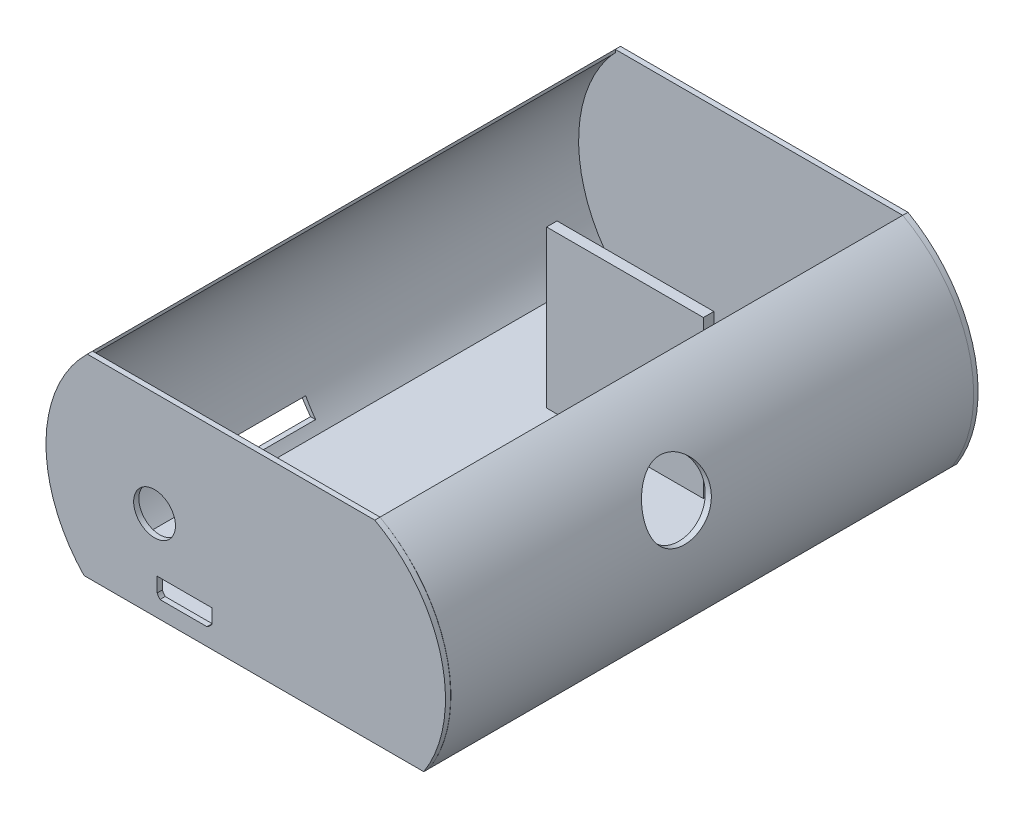
SolidWorks part; units mm, degrees
ref_plane "Front Plane" through (0, 0, 0) normal (0, 0, 1) x (1, 0, 0)
ref_plane "Top Plane" through (0, 0, 0) normal (0, 1, 0) x (1, 0, 0)
ref_plane "Right Plane" through (0, 0, 0) normal (1, 0, 0) x (0, 0, -1)
sketch "Sketch11" plane through (0, 0, 0) normal (0, 0, 1) x (1, 0, 0)
  line L0 (-50.9258, 31.4368) -> (4.0742, 31.4368)
  line L3 (13.439, -5.5632) -> (-51.561, -5.5632)
  line L4 (-51.013, 30.8355) -> (3.987, 30.8355)
  line L9 (3.987, 30.8355) -> (-51.013, 30.8355)
  line L11 (-51.561, -4.5645) -> (13.439, -4.5645)
  arc A0 (-50.9258, 31.4368) -> (-51.561, -5.5632) centre (-32.98, 12.6232) ccw
  arc A1 (4.0742, 31.4368) -> (13.439, -5.5632) centre (-8.3621, 8.604) cw
  arc A3 (-51.013, 30.8355) -> (-51.561, -4.5645) centre (-31.0337, 12.822) ccw
  arc A4 (3.987, 30.8355) -> (13.439, -4.5645) centre (-10.2712, 8.0666) cw
  point P6 (-46.0039, -5.5632)
  point P8 (4.0848, 31.4053)
  dimension "D3" = 26
  dimension "D4" = 65
  dimension "D5" = 55
  dimension "D6" = 37
  dimension "D7" = 65
  dimension "D9" = 0.9987
  dimension "D18" = 55
  dimension "D23" = 35.4
extrude "Boss-Extrude6" add sketch "Sketch11" along normal blind 100 and the other way blind 0.001
ref_plane "front" through (0, 0, 100) normal (0, 0, 1) x (1, 0, 0)
ref_plane "Plane9" through (0, 31.4368, 0) normal (0, -1, 0) x (-1, 0, 0)
sketch "Buttons" plane through (0, 31.4368, 0) normal (0, -1, 0) x (-1, 0, 0)
  line L5 (50.7065, 0.001) -> (-4.2935, 0.001)
  line L6 (50.7065, 0.001) -> (50.7065, -99.999)
  line L7 (50.7065, -99.999) -> (-4.2935, -99.999)
  line L8 (-4.2935, 0.001) -> (-4.2935, -99.999)
  line L10 (-13.439, 0.001) -> (51.561, 0.001) construction
  dimension "D3" = 0
  dimension "D11" = 55
  dimension "D12" = 100
ref_plane "Plane5" through (17.6379, 0, 0) normal (1, 0, 0) x (0, 0, -1)
sketch "Sketch19" plane through (17.6379, 0, 0) normal (1, 0, 0) x (0, 0, -1)
  line L2 (-100, 31.4368) -> (-100, -5.5632) construction
  line L3 (0.001, -5.5632) -> (-100, -5.5632) construction
  circle A0 centre (-55.2, 17.4368) radius 6.25
  dimension "D1" = 23
  dimension "D3" = 12.5
  dimension "D2" = 44.8
extrude "side button" cut sketch "Sketch19" against normal blind 10
ref_plane "sd card" through (-58.98, 0, 0) normal (-1, 0, 0) x (0, 0, 1)
sketch "Sketch21" plane through (-58.98, 0, 0) normal (-1, 0, 0) x (0, 0, 1)
  line L0 (55.5, -0.0632) -> (68.5, -0.0632)
  line L1 (55.5, -0.0632) -> (55.5, -3.0632)
  line L2 (55.5, -3.0632) -> (68.5, -3.0632)
  line L3 (68.5, -0.0632) -> (68.5, -3.0632)
  line L4 (100, -5.5632) -> (100, 31.4368) construction
  line L6 (-0.001, -5.5632) -> (100, -5.5632) construction
  dimension "D1" = 44.5
  dimension "D2" = 3
  dimension "D3" = 5.5
  dimension "D9" = 13
extrude "sd" cut sketch "Sketch21" against normal blind 10
ref_plane "for top cover layer" through (0, 0, -0.001) normal (0, 0, -1) x (-1, 0, 0)
ref_plane "top exclusive" through (0, 31.4368, 0) normal (0, 1, 0) x (1, 0, 0)
sketch "草图4" plane through (0, 0, 100) normal (0, 0, 1) x (1, 0, 0)
  line L0 (-50.9258, 31.4368) -> (4.0742, 31.4368)
  line L1 (13.439, -5.5632) -> (-51.561, -5.5632)
  line L2 (-37.561, 1.3328) -> (-27.1017, 1.3328)
  line L3 (-37.561, 1.3328) -> (-37.561, -1.4468)
  line L4 (-27.1017, 1.3328) -> (-27.1017, -1.4468)
  line L5 (-37.0287, -2.2713) -> (-28.0296, -2.2713)
  arc A0 (-50.9258, 31.4368) -> (-51.561, -5.5632) centre (-32.4656, 12.6144) ccw
  arc A1 (4.0742, 31.4368) -> (13.439, -5.5632) centre (-8.5033, 8.5682) cw
  circle A2 centre (-38.061, 11.4368) radius 4
  arc A3 (-37.561, -1.4468) -> (-37.0287, -2.2713) centre (-34.7289, -0.2026) ccw
  arc A4 (-27.1017, -1.4468) -> (-28.0296, -2.2713) centre (-29.5318, 0.3535) cw
  point P6 (-47.4797, -5.5632)
  point P11 (-38.061, 7.4368)
  point P12 (-42.061, 11.4368)
  dimension "D3" = 8
  dimension "D1" = 65
  dimension "D2" = 55
  dimension "D4" = 17
  dimension "D5" = 14
  dimension "D6" = 13.5
sketch "草图5" plane through (0, 31.4368, 0) normal (0, 1, 0) x (1, 0, 0)
  line L1 (-50.9258, 0.001) -> (4.0742, 0.001)
  line L2 (-50.9258, 0.001) -> (-50.9258, -100)
  line L3 (-50.9258, -100) -> (4.0742, -100)
  line L4 (4.0742, 0.001) -> (4.0742, -100)
extrude "切除-拉伸4" cut sketch "草图5" against normal blind 7
extrude "ports" add sketch "草图4" along normal blind 1
sketch "草图6" plane through (0, 0, -0.001) normal (0, 0, -1) x (-1, 0, 0)
  line L0 (-4.0742, 31.4368) -> (50.9258, 31.4368)
  line L1 (51.561, -5.5632) -> (-13.439, -5.5632)
  arc A0 (-4.0742, 31.4368) -> (-13.439, -5.5632) centre (8.8775, 8.4735) ccw
  arc A1 (50.9258, 31.4368) -> (51.561, -5.5632) centre (32.8392, 12.6208) cw
  point P6 (-8.649, -5.5632)
  dimension "D1" = 65
  dimension "D2" = 55
extrude "top cover " add sketch "草图6" along normal blind 1
ref_plane "inner obstacle" through (0, -4.5645, 0) normal (0, 1, 0) x (1, 0, 0)
sketch "草图7" plane through (0, -4.5645, 0) normal (0, 1, 0) x (1, 0, 0)
  line L0 (-51.561, -100) -> (13.439, -100) construction
  line L1 (-34.061, -28) -> (-4.061, -28)
  line L2 (-34.061, -28) -> (-34.061, -30)
  line L3 (-34.061, -30) -> (-4.061, -30)
  line L4 (-4.061, -28) -> (-4.061, -30)
  line L5 (-51.561, 0.001) -> (-51.561, -100) construction
  dimension "D1" = 30
  dimension "D2" = 2
  dimension "D3" = 70
  dimension "D4" = 17.5
extrude "凸台-拉伸5" add sketch "草图7" along normal blind 30
